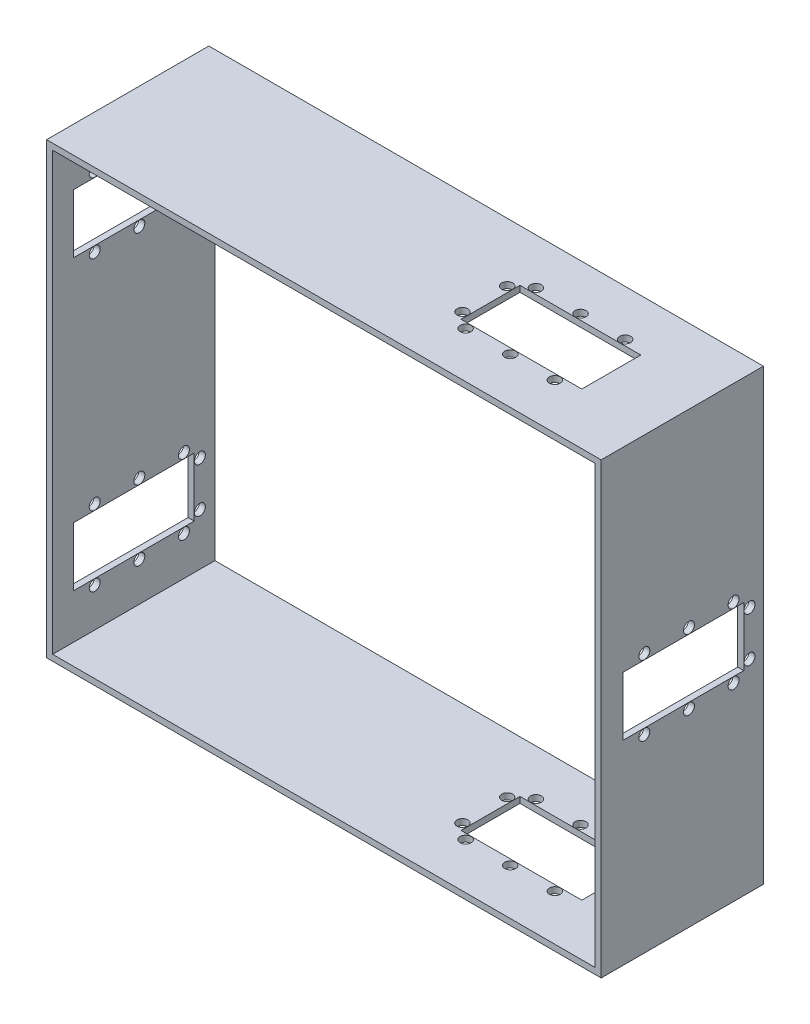
SolidWorks part; units mm, degrees
ref_plane "Plano frontal" through (0, 0, 0) normal (0, 0, 1) x (1, 0, 0)
ref_plane "Plano superior" through (0, 0, 0) normal (0, 1, 0) x (1, 0, 0)
ref_plane "Plano direito" through (0, 0, 0) normal (1, 0, 0) x (0, 0, -1)
sketch "Esboço2" plane through (0, 0, 0) normal (0, 0, 1) x (1, 0, 0)
  line L1 (-136.71, -110.62) -> (136.71, -110.62)
  line L2 (-136.71, -110.62) -> (-136.71, 110.62)
  line L3 (-136.71, 110.62) -> (136.71, 110.62)
  line L4 (136.71, -110.62) -> (136.71, 110.62)
  line L5 (-136.71, -110.62) -> (136.71, 110.62) construction
  line L6 (-136.71, 110.62) -> (136.71, -110.62) construction
  point P0 (0, 0)
extrude "Ressalto-extrusão1" add sketch "Esboço2" along normal blind 80
sketch "Esboço3" plane through (0, 0, 0) normal (0, 0, 1) x (1, 0, 0)
  line L1 (-133.71, -107.62) -> (133.71, -107.62)
  line L2 (-133.71, -107.62) -> (-133.71, 107.62)
  line L3 (-133.71, 107.62) -> (133.71, 107.62)
  line L4 (133.71, -107.62) -> (133.71, 107.62)
  line L5 (-133.71, -107.62) -> (133.71, 107.62) construction
  line L6 (-133.71, 107.62) -> (133.71, -107.62) construction
  point P0 (0, 0)
extrude "Corte-extrusão1" cut sketch "Esboço3" along normal blind 80
sketch "Esboço4" plane through (0, 0, 0) normal (1, 0, 0) x (0, 0, -1)
  line L2 (-69.2146, -14.525) -> (-9.6646, -14.525)
  line L3 (-69.2146, -14.525) -> (-69.2146, 14.525)
  line L4 (-69.2146, 14.525) -> (-9.6646, 14.525)
  line L5 (-9.6646, -14.525) -> (-9.6646, 14.525)
  line L6 (-69.2146, -14.525) -> (-9.6646, 14.525) construction
  line L7 (-69.2146, 14.525) -> (-9.6646, -14.525) construction
  point P0 (-39.4396, 0)
  point P2 (0, 0)
extrude "Corte-extrusão3" cut sketch "Esboço4" along normal through all
sketch "Esboço5" plane through (0, 0, 0) normal (1, 0, 0) x (0, 0, -1)
  line L0 (-69.775, 56.57) -> (-10.225, 56.57)
  line L1 (-69.775, 56.57) -> (-69.775, 85.62)
  line L2 (-69.775, 85.62) -> (-10.225, 85.62)
  line L3 (-10.225, 56.57) -> (-10.225, 85.62)
  line L4 (-69.775, -85.62) -> (-10.225, -85.62)
  line L5 (-69.775, -85.62) -> (-69.775, -56.57)
  line L6 (-69.775, -56.57) -> (-10.225, -56.57)
  line L7 (-10.225, -85.62) -> (-10.225, -56.57)
  line L8 (-69.775, 85.62) -> (-10.225, 56.57) construction
  line L9 (-10.225, 85.62) -> (-69.775, 56.57) construction
  line L10 (-69.775, -56.57) -> (-10.225, -85.62) construction
  line L11 (-10.225, -56.57) -> (-69.775, -85.62) construction
  line L12 (-80, 110.62) -> (0, 110.62) construction
  line L13 (-80, -110.62) -> (0, -110.62) construction
  point P8 (-40, 71.095)
  point P9 (-40, -71.095)
  point P12 (-40, 110.62)
  dimension "D1" = 29.05
  dimension "D2" = 29.05
  dimension "D3" = 25
  dimension "D4" = 59.55
  dimension "D5" = 25
extrude "Corte-extrusão4" cut sketch "Esboço5" against normal through all
sketch "Esboço6" plane through (0, 0, 0) normal (0, 1, 0) x (1, 0, 0)
  line L0 (136.71, -80) -> (136.71, 0) construction
  line L1 (42.16, -25.475) -> (101.71, -25.475)
  line L2 (42.16, -25.475) -> (42.16, -54.525)
  line L3 (42.16, -54.525) -> (101.71, -54.525)
  line L4 (101.71, -25.475) -> (101.71, -54.525)
  line L5 (42.16, -25.475) -> (101.71, -54.525) construction
  line L6 (42.16, -54.525) -> (101.71, -25.475) construction
  point P0 (71.935, -40)
  point P5 (0, 0)
  point P8 (136.71, -40)
  dimension "D1" = 59.55
  dimension "D2" = 35
extrude "Corte-extrusão5" cut sketch "Esboço6" against normal through all both and the other way through all
sketch "Esboço7" plane through (0, 0, 0) normal (0, 1, 0) x (1, 0, 0)
  line L0 (101.71, -54.525) -> (101.71, -25.475) construction
  line L2 (101.71, -25.475) -> (42.16, -25.475) construction
  line L4 (101.71, -40) -> (42.16, -40) construction
  line L5 (42.16, -25.475) -> (42.16, -54.525) construction
  circle A0 centre (91.21, -22.675) radius 2.7
  circle A1 centre (69.21, -22.675) radius 2.7
  circle A2 centre (47.21, -22.675) radius 2.7
  circle A3 centre (91.21, -57.325) radius 2.7
  circle A4 centre (69.21, -57.325) radius 2.7
  circle A5 centre (47.21, -57.325) radius 2.7
  circle A6 centre (39.36, -28.975) radius 2.7
  circle A7 centre (39.36, -51.025) radius 2.7
  dimension "D1" = 10.5
  dimension "D4" = 3.5
  dimension "D6" = 10.0654
  dimension "D2" = 2.8
  dimension "D5" = 2.8
  dimension "D3" = 3
extrude "Corte-extrusão6" cut sketch "Esboço7" against normal through all both and the other way through all
sketch "Esboço8" plane through (0, 0, 0) normal (1, 0, 0) x (0, 0, -1)
  line L0 (-69.775, -71.095) -> (-10.225, -71.095) construction
  line L1 (-69.775, -56.57) -> (-69.775, -85.62) construction
  line L2 (-69.2146, 14.525) -> (-69.2146, -14.525) construction
  line L4 (-69.2146, 0) -> (-9.6646, 0) construction
  line L5 (-9.6646, -14.525) -> (-9.6646, 14.525) construction
  line L6 (-10.225, -85.62) -> (-10.225, -56.57) construction
  line L7 (-69.775, 71.095) -> (-10.225, 71.095) construction
  line L8 (-69.775, 85.62) -> (-69.775, 56.57) construction
  line L9 (-10.225, 56.57) -> (-10.225, 85.62) construction
  line L10 (-69.775, -85.62) -> (-10.225, -85.62) construction
  circle A9 centre (-59.275, -88.42) radius 2.7
  circle A10 centre (-37.275, -88.42) radius 2.7
  circle A11 centre (-15.275, -88.42) radius 2.7
  circle A12 centre (-15.275, -53.77) radius 2.7
  circle A13 centre (-37.275, -53.77) radius 2.7
  circle A14 centre (-59.275, -53.77) radius 2.7
  circle A15 centre (-7.425, -82.12) radius 2.7
  circle A16 centre (-7.425, -60.07) radius 2.7
  circle A17 centre (-59.275, 53.77) radius 2.7
  circle A18 centre (-37.275, 53.77) radius 2.7
  circle A19 centre (-15.275, 53.77) radius 2.7
  circle A20 centre (-7.425, 60.07) radius 2.7
  circle A21 centre (-7.425, 82.12) radius 2.7
  circle A22 centre (-15.275, 88.42) radius 2.7
  circle A23 centre (-37.275, 88.42) radius 2.7
  circle A24 centre (-59.275, 88.42) radius 2.7
  point P18 (0, 0)
  point P52 (-6.8646, -79.6056)
  point P73 (0, 0)
  point P74 (0, 0)
  point P75 (0, 0)
  point P76 (0, 0)
  dimension "D6" = 10.5
  dimension "D7" = 2.8
  dimension "D9" = 3.5
  dimension "D10" = 2.8
  dimension "D8" = 3
extrude "Corte-extrusão7" cut sketch "Esboço8" against normal through all
sketch "Esboço9" plane through (0, 0, 0) normal (1, 0, 0) x (0, 0, -1)
  line L0 (-69.2146, 14.525) -> (-69.2146, -14.525) construction
  line L1 (-9.6646, 14.525) -> (-69.2146, 14.525) construction
  line L2 (-69.2146, 0) -> (-9.6646, 0) construction
  line L3 (-9.6646, -14.525) -> (-9.6646, 14.525) construction
  circle A0 centre (-58.7146, 17.325) radius 2.7
  circle A1 centre (-36.7146, 17.325) radius 2.7
  circle A2 centre (-14.7146, 17.325) radius 2.7
  circle A3 centre (-14.7146, -17.325) radius 2.7
  circle A4 centre (-36.7146, -17.325) radius 2.7
  circle A5 centre (-58.7146, -17.325) radius 2.7
  circle A6 centre (-6.8646, 11.025) radius 2.7
  circle A7 centre (-6.8646, -11.025) radius 2.7
  dimension "D1" = 10.5
  dimension "D4" = 3.5
  dimension "D2" = 2.8
  dimension "D5" = 2.8
  dimension "D3" = 3
extrude "Corte-extrusão8" cut sketch "Esboço9" along normal through all
